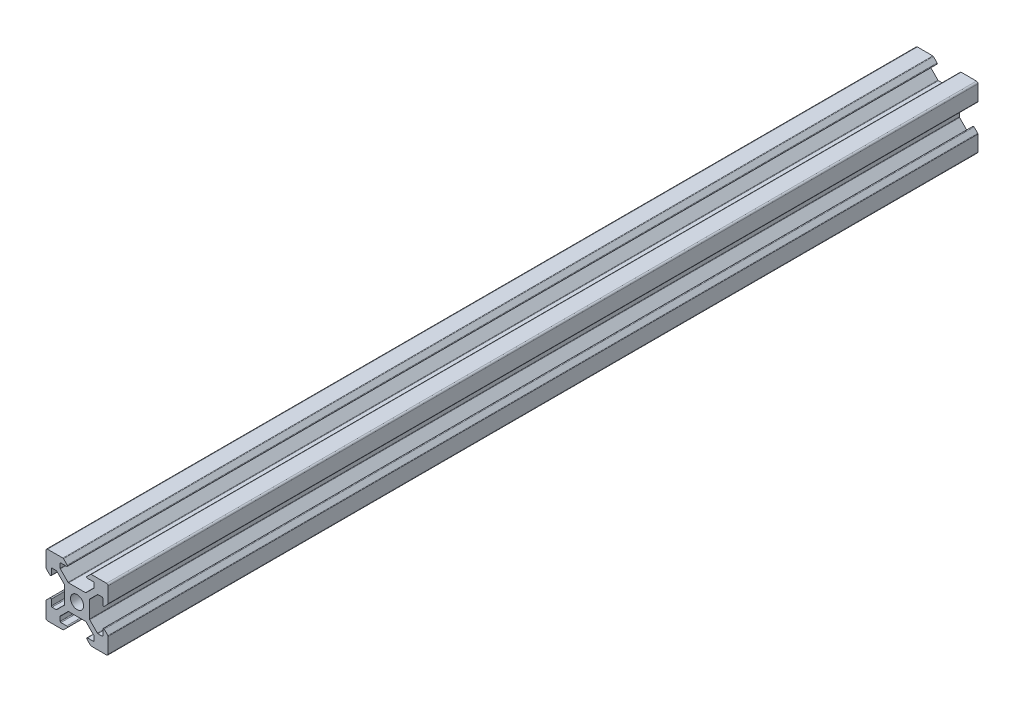
SolidWorks part; units mm, degrees
material "1060 Alloy"
ref_plane "Front Plane" through (0, 0, 0) normal (0, 0, 1) x (1, 0, 0)
ref_plane "Top Plane" through (0, 0, 0) normal (0, 1, 0) x (1, 0, 0)
ref_plane "Right Plane" through (0, 0, 0) normal (1, 0, 0) x (0, 0, -1)
sketch "Model" plane through (0, 0, 0) normal (0, 0, 1) x (1, 0, 0)
  line L0 (2012.9312, 1381.8004) -> (2012.9312, 1378.2004)
  line L1 (2016.4702, 1376.0004) -> (2017.3922, 1376.0004)
  line L2 (2020.9312, 1380.4614) -> (2020.9312, 1379.5394)
  line L3 (2016.4702, 1384.0004) -> (2017.3922, 1384.0004)
  line L270 (2012.9312, 1381.8004) -> (2012.9312, 1382.7004)
  line L271 (2012.8433, 1382.9125) -> (2010.3787, 1385.3772)
  line L272 (2010.2019, 1385.4504) -> (2008.8812, 1385.4504)
  line L273 (2008.6312, 1385.2004) -> (2008.6312, 1383.3504)
  line L274 (2008.2044, 1383.1736) -> (2007.0191, 1384.359)
  line L275 (2006.9312, 1384.5711) -> (2006.9312, 1389.5004)
  line L276 (2007.4312, 1390.0004) -> (2012.3605, 1390.0004)
  line L277 (2012.5726, 1389.9125) -> (2013.758, 1388.7272)
  line L278 (2013.5812, 1388.3004) -> (2011.7312, 1388.3004)
  line L279 (2011.4812, 1388.0504) -> (2011.4812, 1386.7297)
  line L280 (2011.5544, 1386.5529) -> (2014.0338, 1384.0736)
  line L281 (2014.2105, 1384.0004) -> (2016.4702, 1384.0004)
  line L282 (2017.3922, 1384.0004) -> (2019.6519, 1384.0004)
  line L283 (2019.8287, 1384.0736) -> (2022.308, 1386.5529)
  line L284 (2022.3812, 1386.7297) -> (2022.3812, 1388.0504)
  line L285 (2022.1312, 1388.3004) -> (2020.2812, 1388.3004)
  line L286 (2020.1044, 1388.7272) -> (2021.2898, 1389.9125)
  line L287 (2021.5019, 1390.0004) -> (2026.4312, 1390.0004)
  line L288 (2026.9312, 1389.5004) -> (2026.9312, 1384.5711)
  line L289 (2026.8433, 1384.359) -> (2025.658, 1383.1736)
  line L290 (2025.2312, 1383.3504) -> (2025.2312, 1385.2004)
  line L291 (2024.9812, 1385.4504) -> (2023.6605, 1385.4504)
  line L292 (2023.4838, 1385.3772) -> (2021.0044, 1382.8978)
  line L293 (2020.9312, 1382.7211) -> (2020.9312, 1380.4614)
  line L294 (2020.9312, 1379.5394) -> (2020.9312, 1377.2797)
  line L295 (2021.0044, 1377.1029) -> (2023.4838, 1374.6236)
  line L296 (2023.6605, 1374.5504) -> (2024.9812, 1374.5504)
  line L297 (2025.2312, 1374.8004) -> (2025.2312, 1376.6504)
  line L298 (2025.658, 1376.8272) -> (2026.8433, 1375.6418)
  line L299 (2026.9312, 1375.4297) -> (2026.9312, 1370.5004)
  line L300 (2026.4312, 1370.0004) -> (2021.5019, 1370.0004)
  line L301 (2021.2898, 1370.0883) -> (2020.1044, 1371.2736)
  line L302 (2020.2812, 1371.7004) -> (2022.1312, 1371.7004)
  line L303 (2022.3812, 1371.9504) -> (2022.3812, 1373.2711)
  line L304 (2022.308, 1373.4478) -> (2019.8287, 1375.9272)
  line L305 (2019.6519, 1376.0004) -> (2017.3922, 1376.0004)
  line L306 (2016.4702, 1376.0004) -> (2014.2105, 1376.0004)
  line L307 (2014.0338, 1375.9272) -> (2011.5544, 1373.4478)
  line L308 (2011.4812, 1373.2711) -> (2011.4812, 1371.9504)
  line L309 (2011.7312, 1371.7004) -> (2013.5812, 1371.7004)
  line L310 (2013.758, 1371.2736) -> (2012.5726, 1370.0883)
  line L311 (2012.3605, 1370.0004) -> (2007.4312, 1370.0004)
  line L312 (2006.9312, 1370.5004) -> (2006.9312, 1375.4297)
  line L313 (2007.0191, 1375.6418) -> (2008.2044, 1376.8272)
  line L314 (2008.6312, 1376.6504) -> (2008.6312, 1374.8004)
  line L315 (2008.8812, 1374.5504) -> (2010.2019, 1374.5504)
  line L316 (2010.3787, 1374.6236) -> (2012.8433, 1377.0883)
  line L317 (2012.9312, 1377.3004) -> (2012.9312, 1378.2004)
  circle A0 centre (2016.9312, 1380.0004) radius 2.1
  arc A427 (2012.9312, 1382.7004) -> (2012.8433, 1382.9125) centre (2012.6312, 1382.7004) ccw
  arc A428 (2010.3787, 1385.3772) -> (2010.2019, 1385.4504) centre (2010.2019, 1385.2004) ccw
  arc A429 (2008.8812, 1385.4504) -> (2008.6312, 1385.2004) centre (2008.8812, 1385.2004) ccw
  arc A430 (2008.2044, 1383.1736) -> (2008.6312, 1383.3504) centre (2008.3812, 1383.3504) ccw
  arc A431 (2006.9312, 1384.5711) -> (2007.0191, 1384.359) centre (2007.2312, 1384.5711) ccw
  arc A432 (2007.4312, 1390.0004) -> (2006.9312, 1389.5004) centre (2007.4312, 1389.5004) ccw
  arc A433 (2012.5726, 1389.9125) -> (2012.3605, 1390.0004) centre (2012.3605, 1389.7004) ccw
  arc A434 (2013.5812, 1388.3004) -> (2013.758, 1388.7272) centre (2013.5812, 1388.5504) ccw
  arc A435 (2011.7312, 1388.3004) -> (2011.4812, 1388.0504) centre (2011.7312, 1388.0504) ccw
  arc A436 (2011.4812, 1386.7297) -> (2011.5544, 1386.5529) centre (2011.7312, 1386.7297) ccw
  arc A437 (2014.0338, 1384.0736) -> (2014.2105, 1384.0004) centre (2014.2105, 1384.2504) ccw
  arc A441 (2019.6519, 1384.0004) -> (2019.8287, 1384.0736) centre (2019.6519, 1384.2504) ccw
  arc A442 (2022.308, 1386.5529) -> (2022.3812, 1386.7297) centre (2022.1312, 1386.7297) ccw
  arc A443 (2022.3812, 1388.0504) -> (2022.1312, 1388.3004) centre (2022.1312, 1388.0504) ccw
  arc A444 (2020.1044, 1388.7272) -> (2020.2812, 1388.3004) centre (2020.2812, 1388.5504) ccw
  arc A445 (2021.5019, 1390.0004) -> (2021.2898, 1389.9125) centre (2021.5019, 1389.7004) ccw
  arc A446 (2026.9312, 1389.5004) -> (2026.4312, 1390.0004) centre (2026.4312, 1389.5004) ccw
  arc A447 (2026.8433, 1384.359) -> (2026.9312, 1384.5711) centre (2026.6312, 1384.5711) ccw
  arc A448 (2025.2312, 1383.3504) -> (2025.658, 1383.1736) centre (2025.4812, 1383.3504) ccw
  arc A449 (2025.2312, 1385.2004) -> (2024.9812, 1385.4504) centre (2024.9812, 1385.2004) ccw
  arc A450 (2023.6605, 1385.4504) -> (2023.4838, 1385.3772) centre (2023.6605, 1385.2004) ccw
  arc A451 (2021.0044, 1382.8978) -> (2020.9312, 1382.7211) centre (2021.1812, 1382.7211) ccw
  arc A455 (2020.9312, 1377.2797) -> (2021.0044, 1377.1029) centre (2021.1812, 1377.2797) ccw
  arc A456 (2023.4838, 1374.6236) -> (2023.6605, 1374.5504) centre (2023.6605, 1374.8004) ccw
  arc A457 (2024.9812, 1374.5504) -> (2025.2312, 1374.8004) centre (2024.9812, 1374.8004) ccw
  arc A458 (2025.658, 1376.8272) -> (2025.2312, 1376.6504) centre (2025.4812, 1376.6504) ccw
  arc A459 (2026.9312, 1375.4297) -> (2026.8433, 1375.6418) centre (2026.6312, 1375.4297) ccw
  arc A460 (2026.4312, 1370.0004) -> (2026.9312, 1370.5004) centre (2026.4312, 1370.5004) ccw
  arc A461 (2021.2898, 1370.0883) -> (2021.5019, 1370.0004) centre (2021.5019, 1370.3004) ccw
  arc A462 (2020.2812, 1371.7004) -> (2020.1044, 1371.2736) centre (2020.2812, 1371.4504) ccw
  arc A463 (2022.1312, 1371.7004) -> (2022.3812, 1371.9504) centre (2022.1312, 1371.9504) ccw
  arc A464 (2022.3812, 1373.2711) -> (2022.308, 1373.4478) centre (2022.1312, 1373.2711) ccw
  arc A465 (2019.8287, 1375.9272) -> (2019.6519, 1376.0004) centre (2019.6519, 1375.7504) ccw
  arc A469 (2014.2105, 1376.0004) -> (2014.0338, 1375.9272) centre (2014.2105, 1375.7504) ccw
  arc A470 (2011.5544, 1373.4478) -> (2011.4812, 1373.2711) centre (2011.7312, 1373.2711) ccw
  arc A471 (2011.4812, 1371.9504) -> (2011.7312, 1371.7004) centre (2011.7312, 1371.9504) ccw
  arc A472 (2013.758, 1371.2736) -> (2013.5812, 1371.7004) centre (2013.5812, 1371.4504) ccw
  arc A473 (2012.3605, 1370.0004) -> (2012.5726, 1370.0883) centre (2012.3605, 1370.3004) ccw
  arc A474 (2006.9312, 1370.5004) -> (2007.4312, 1370.0004) centre (2007.4312, 1370.5004) ccw
  arc A475 (2007.0191, 1375.6418) -> (2006.9312, 1375.4297) centre (2007.2312, 1375.4297) ccw
  arc A476 (2008.6312, 1376.6504) -> (2008.2044, 1376.8272) centre (2008.3812, 1376.6504) ccw
  arc A477 (2008.6312, 1374.8004) -> (2008.8812, 1374.5504) centre (2008.8812, 1374.8004) ccw
  arc A478 (2010.2019, 1374.5504) -> (2010.3787, 1374.6236) centre (2010.2019, 1374.8004) ccw
  arc A479 (2012.8433, 1377.0883) -> (2012.9312, 1377.3004) centre (2012.6312, 1377.3004) ccw
extrude "Boss-Extrude1" add sketch "Model" along normal blind 280
